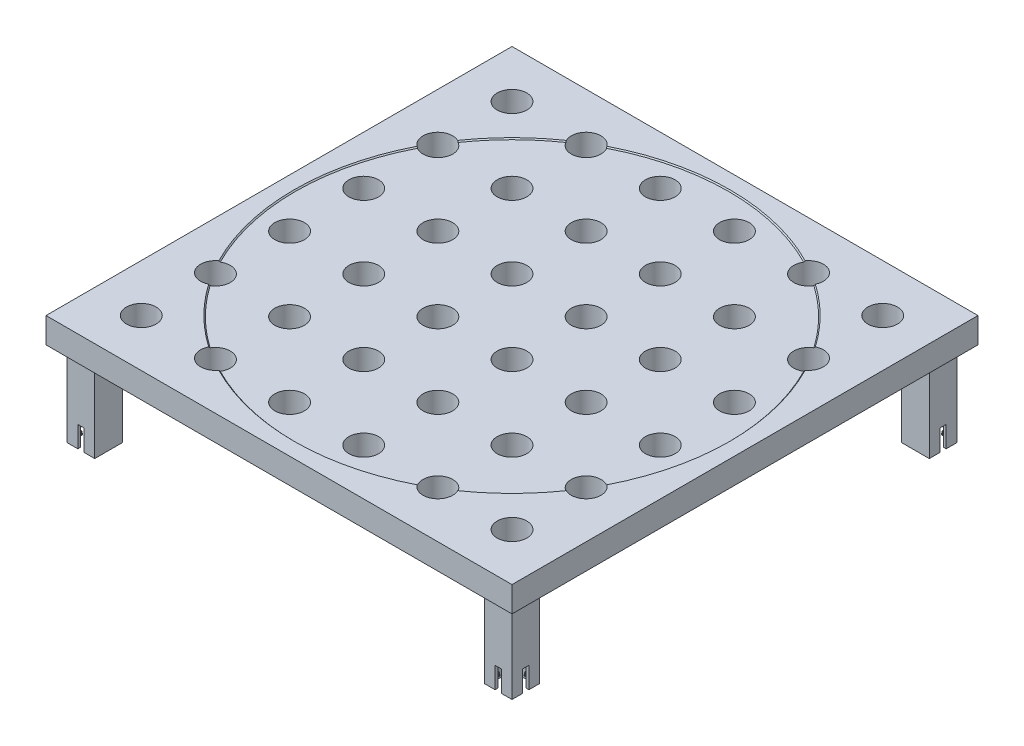
SolidWorks part; units mm, degrees
ref_plane "Front Plane" through (0, 0, 0) normal (0, 0, 1) x (1, 0, 0)
ref_plane "Top Plane" through (0, 0, 0) normal (0, 1, 0) x (1, 0, 0)
ref_plane "Right Plane" through (0, 0, 0) normal (1, 0, 0) x (0, 0, -1)
sketch "Sketch1" plane through (0, 0, 0) normal (0, 1, 0) x (1, 0, 0)
  line L1 (86.2993, -115.6122) -> (-133.7007, -115.6122)
  line L2 (86.2993, -115.6122) -> (86.2993, 104.3878)
  line L3 (86.2993, 104.3878) -> (-133.7007, 104.3878)
  line L4 (-133.7007, -115.6122) -> (-133.7007, 104.3878)
  line L5 (86.2993, -115.6122) -> (-133.7007, 104.3878) construction
  line L6 (86.2993, 104.3878) -> (-133.7007, -115.6122) construction
  point P0 (-23.7007, -5.6122)
  dimension "D1" = 220
  dimension "D2" = 220
extrude "Boss-Extrude1" add sketch "Sketch1" along normal blind 12
sketch "Sketch2" plane through (0, 12, 0) normal (0, 1, 0) x (1, 0, 0)
  line L0 (-111.2007, 104.3878) -> (-111.2007, 88.8878) construction
  line L1 (86.2993, 104.3878) -> (-133.7007, 104.3878) construction
  line L2 (-111.2007, 88.8878) -> (-111.2007, 81.8878) construction
  line L3 (-111.2007, 81.8878) -> (-118.2007, 81.8878) construction
  line L4 (-118.2007, 81.8878) -> (-133.7007, 81.8878) construction
  line L5 (-133.7007, 104.3878) -> (-133.7007, -115.6122) construction
  circle A0 centre (-111.2007, 81.8878) radius 7
  dimension "D1" = 14
  dimension "D2" = 15.5
extrude "Cut-Extrude1" cut sketch "Sketch2" against normal through all
pattern_linear "LPattern1" count 6 spacing 35 along (1, 0, 0) count 6 spacing 35 along (0, 0, 1) of "Cut-Extrude1"
sketch "Sketch4" plane through (0, 12, 0) normal (0, 1, 0) x (1, 0, 0)
  line L0 (-23.7007, 104.3878) -> (-23.7007, -5.6122) construction
  line L1 (86.2993, 104.3878) -> (-133.7007, 104.3878) construction
  line L2 (-23.7007, -5.6122) -> (86.2993, -5.6122) construction
  line L3 (86.2993, -115.6122) -> (86.2993, 104.3878) construction
  circle A0 centre (-23.7007, -5.6122) radius 102.87
  dimension "D1" = 205.74
extrude "Cut-Extrude2" cut sketch "Sketch4" against normal blind 0.5 draft 45 contours A0
sketch "Sketch5" plane through (0, 0, 0) normal (0, -1, 0) x (-1, 0, 0)
  line L0 (128.7007, -104.1122) -> (133.7007, -104.1122) construction
  line L6 (133.7007, 104.3878) -> (133.7007, -115.6122) construction
  line L7 (115.7007, -110.6122) -> (128.7007, -110.6122)
  line L8 (115.7007, -110.6122) -> (115.7007, -97.6122)
  line L9 (115.7007, -97.6122) -> (128.7007, -97.6122)
  line L10 (128.7007, -110.6122) -> (128.7007, -97.6122)
  line L11 (122.2007, -97.6122) -> (122.2007, -110.6122) construction
  line L12 (115.7007, -104.1122) -> (128.7007, -104.1122) construction
  line L13 (127.3507, -109.2622) -> (117.0507, -109.2622)
  line L14 (122.2007, -110.6122) -> (122.2007, -115.6122) construction
  line L15 (133.7007, -115.6122) -> (-86.2993, -115.6122) construction
  line L16 (127.3507, -109.2622) -> (127.3507, -98.9622)
  line L17 (127.3507, -98.9622) -> (117.0507, -98.9622)
  line L18 (117.0507, -109.2622) -> (117.0507, -98.9622)
  line L19 (127.3507, -109.2622) -> (117.0507, -98.9622) construction
  line L20 (127.3507, -98.9622) -> (117.0507, -109.2622) construction
  point P0 (130.0171, -137.8684)
  point P4 (122.2007, -104.1122)
  point P65 (122.2007, -104.1122)
  dimension "D1" = 13
  dimension "D2" = 13
  dimension "5" = 5
  dimension "D3" = 10.3
  dimension "D4" = 10.3
extrude "Boss-Extrude2" add sketch "Sketch5" along normal blind 40
ref_plane "Plane2" through (0, 0, 5.6122) normal (0, 0, 1) x (1, 0, 0)
ref_plane "Plane3" through (-23.7007, 0, 0) normal (1, 0, 0) x (0, 0, -1)
sketch "Sketch6" plane through (-128.7007, 0, 0) normal (-1, 0, 0) x (0, 0, 1)
  line L0 (110.6122, -40) -> (97.6122, -40) construction
  line L1 (102.6122, -30) -> (105.6122, -30)
  line L2 (102.6122, -30) -> (102.6122, -40)
  line L3 (102.6122, -40) -> (105.6122, -40)
  line L4 (105.6122, -30) -> (105.6122, -40)
  line L5 (104.1122, -40) -> (104.1122, -30) construction
  line L6 (102.6122, -35) -> (105.6122, -35) construction
  line L7 (102.6122, -35) -> (97.6122, -35) construction
  line L8 (97.6122, -40) -> (97.6122, 0) construction
  line L9 (105.6122, -35) -> (110.6122, -35) construction
  line L10 (110.6122, -40) -> (110.6122, 0) construction
  point P200 (104.1122, -35)
  dimension "D1" = 3
  dimension "D2" = 10
extrude "Cut-Extrude3" cut sketch "Sketch6" against normal blind 1.5
sketch "Sketch7" plane through (0, 0, 110.6122) normal (0, 0, 1) x (1, 0, 0)
  line L0 (-115.7007, -40) -> (-128.7007, -40) construction
  line L1 (-123.7007, -40) -> (-120.7007, -40)
  line L2 (-123.7007, -40) -> (-123.7007, -30)
  line L3 (-123.7007, -30) -> (-120.7007, -30)
  line L4 (-120.7007, -40) -> (-120.7007, -30)
  line L5 (-122.2007, -30) -> (-122.2007, -40) construction
  line L6 (-123.7007, -35) -> (-120.7007, -35) construction
  line L7 (-123.7007, -35) -> (-128.7007, -35) construction
  line L8 (-128.7007, -40) -> (-128.7007, 0) construction
  line L9 (-120.7007, -35) -> (-115.7007, -35) construction
  line L10 (-115.7007, -40) -> (-115.7007, 0) construction
  point P248 (-122.2007, -35)
  dimension "D1" = 3
  dimension "D2" = 10
extrude "Cut-Extrude4" cut sketch "Sketch7" against normal blind 1.5
sketch "Sketch11" plane through (0, 0, 102.6122) normal (0, 0, 1) x (1, 0, 0)
  line L0 (-127.3507, -33) -> (-126.8507, -35)
  line L2 (-126.8507, -35) -> (-127.3507, -35)
  line L3 (-127.3507, -35) -> (-127.3507, -33)
  line L4 (-127.3507, -40) -> (-127.3507, -30) construction
  dimension "D1" = 2
  dimension "D2" = 0.5
  dimension "D3" = 5
extrude "Boss-Extrude3" add sketch "Sketch11" along normal blind 0.5 and the other way blind 0.5
ref_plane "Plane5" through (0, 0, 104.1122) normal (0, 0, 1) x (1, 0, 0)
sketch "Sketch12" plane through (-123.7007, 0, 0) normal (1, 0, 0) x (0, 0, -1)
  line L0 (-109.2622, -33) -> (-108.7622, -35)
  line L1 (-109.2622, -40) -> (-109.2622, -30) construction
  line L2 (-108.7622, -35) -> (-109.2622, -35)
  line L3 (-109.2622, -35) -> (-109.2622, -33)
  line L4 (-109.2622, -40) -> (-109.2622, 0) construction
  dimension "D1" = 2
  dimension "D2" = 0.5
  dimension "D3" = 5
extrude "Boss-Extrude4" add sketch "Sketch12" along normal blind 0.5 and the other way blind 0.5
ref_plane "Plane6" through (-122.2007, 0, 0) normal (1, 0, 0) x (0, 0, -1)
mirror "Mirror3" about plane through (0, 0, 104.1122) normal (0, 0, 1) of "Boss-Extrude3"
mirror "Mirror4" about plane through (-122.2007, 0, 0) normal (1, 0, 0) of "Boss-Extrude4"
mirror "Mirror1" about plane through (0, 0, 5.6122) normal (0, 0, 1) of "Cut-Extrude4", "Cut-Extrude3", "Mirror3", "Mirror4", "Boss-Extrude3", "Boss-Extrude4", "Boss-Extrude2"
mirror "Mirror2" about plane through (-23.7007, 0, 0) normal (1, 0, 0) of "Boss-Extrude4", "Mirror4", "Mirror3", "Boss-Extrude3", "Cut-Extrude4", "Cut-Extrude3", "Boss-Extrude2", "Mirror1"
